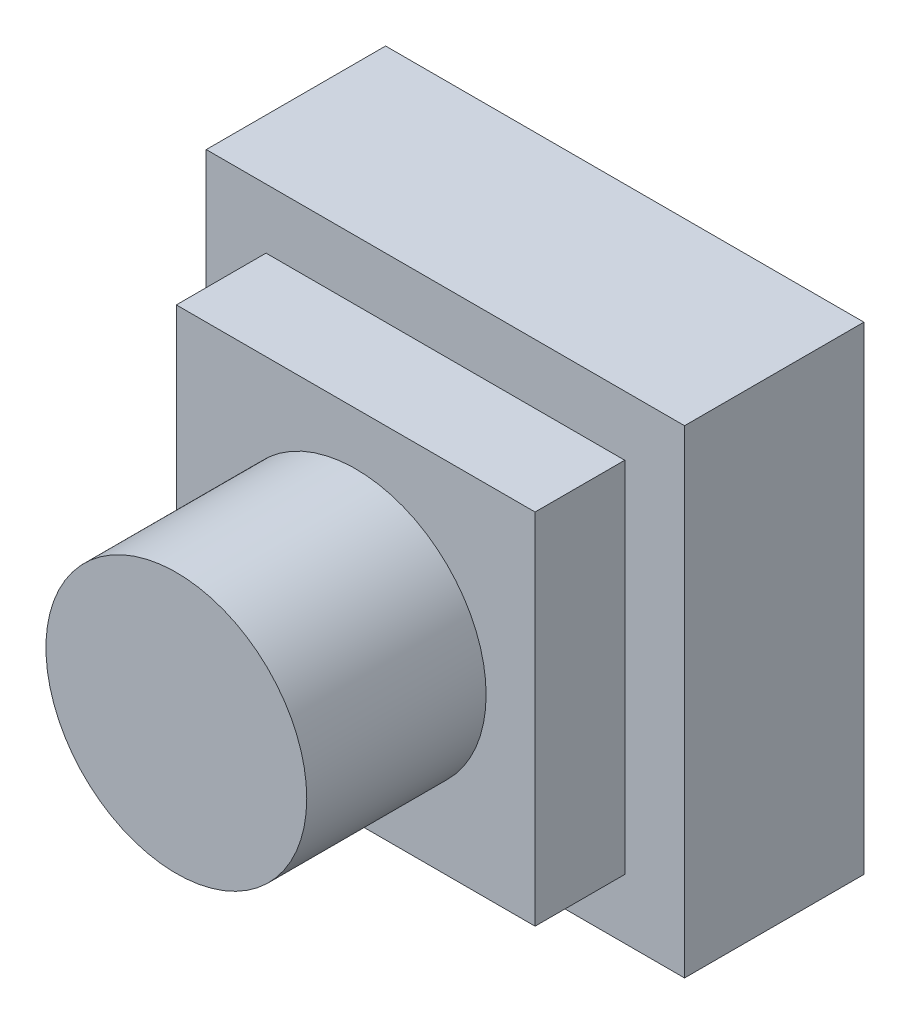
SolidWorks part; units mm, degrees
ref_plane "Front Plane" through (0, 0, 0) normal (0, 0, 1) x (1, 0, 0)
ref_plane "Top Plane" through (0, 0, 0) normal (0, 1, 0) x (1, 0, 0)
ref_plane "Right Plane" through (0, 0, 0) normal (1, 0, 0) x (0, 0, -1)
sketch "Sketch1" plane through (0, 0, 0) normal (0, 0, 1) x (1, 0, 0)
  line L1 (0, 0) -> (6, 0)
  line L2 (0, 0) -> (0, 6)
  line L3 (0, 6) -> (6, 6)
  line L4 (6, 0) -> (6, 6)
  dimension "D1" = 6
  dimension "D2" = 6
extrude "Boss-Extrude1" add sketch "Sketch1" against normal blind 1.5
sketch "Sketch2" plane through (0, 0, 0) normal (0, 0, 1) x (1, 0, 0)
  circle A0 centre (3, 2.9437) radius 2.1812
  point P2 (0, 0)
extrude "Boss-Extrude2" add sketch "Sketch2" along normal blind 3
sketch "Sketch4" plane through (0, 0, -1.5) normal (0, 0, -1) x (-1, 0, 0)
  line L0 (-6, 6) -> (0, 6) construction
  line L1 (-7, 7) -> (1, 7)
  line L2 (-7, 7) -> (-7, -1)
  line L3 (-7, -1) -> (1, -1)
  line L4 (1, 7) -> (1, -1)
  line L5 (0, 6) -> (0, 0) construction
  line L6 (-6, 0) -> (-6, 6) construction
  line L7 (0, 0) -> (-6, 0) construction
  dimension "D1" = 1
  dimension "D2" = 1
  dimension "D3" = 1
  dimension "D4" = 1
extrude "Boss-Extrude3" add sketch "Sketch4" along normal blind 3
